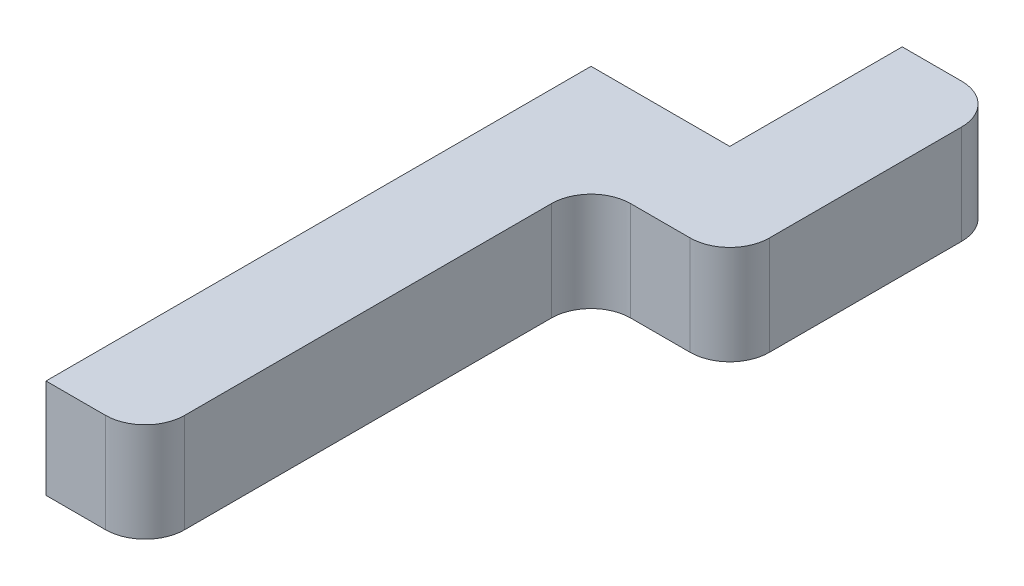
SolidWorks part; units mm, degrees
ref_plane "Front Plane" through (0, 0, 0) normal (0, 0, 1) x (1, 0, 0)
ref_plane "Top Plane" through (0, 0, 0) normal (0, 1, 0) x (1, 0, 0)
ref_plane "Right Plane" through (0, 0, 0) normal (1, 0, 0) x (0, 0, -1)
sketch "Sketch1" plane through (0, 0, 0) normal (0, 1, 0) x (1, 0, 0)
  line L0 (7, 36.2) -> (10, 36.2)
  line L1 (0, 27.5) -> (0, 0)
  line L2 (0, 27.5) -> (7, 27.5)
  line L3 (7, 27.5) -> (7, 36.2)
  line L4 (12, 34.2) -> (12, 24.5)
  line L5 (10, 22.5) -> (7, 22.5)
  line L6 (5, 20.5) -> (5, 2)
  line L7 (3, 0) -> (0, 0)
  arc A0 (10, 36.2) -> (12, 34.2) centre (10, 34.2) cw
  arc A1 (12, 24.5) -> (10, 22.5) centre (10, 24.5) cw
  arc A2 (7, 22.5) -> (5, 20.5) centre (7, 20.5) ccw
  arc A3 (5, 2) -> (3, 0) centre (3, 2) cw
  point P12 (12, 36.2)
  point P19 (5, 0)
  dimension "D7" = 2
  dimension "D1" = 5
  dimension "D2" = 27.5
  dimension "D3" = 7
  dimension "D4" = 36.2
  dimension "D5" = 5
  dimension "D6" = 5
extrude "Boss-Extrude1" add sketch "Sketch1" along normal blind 5
